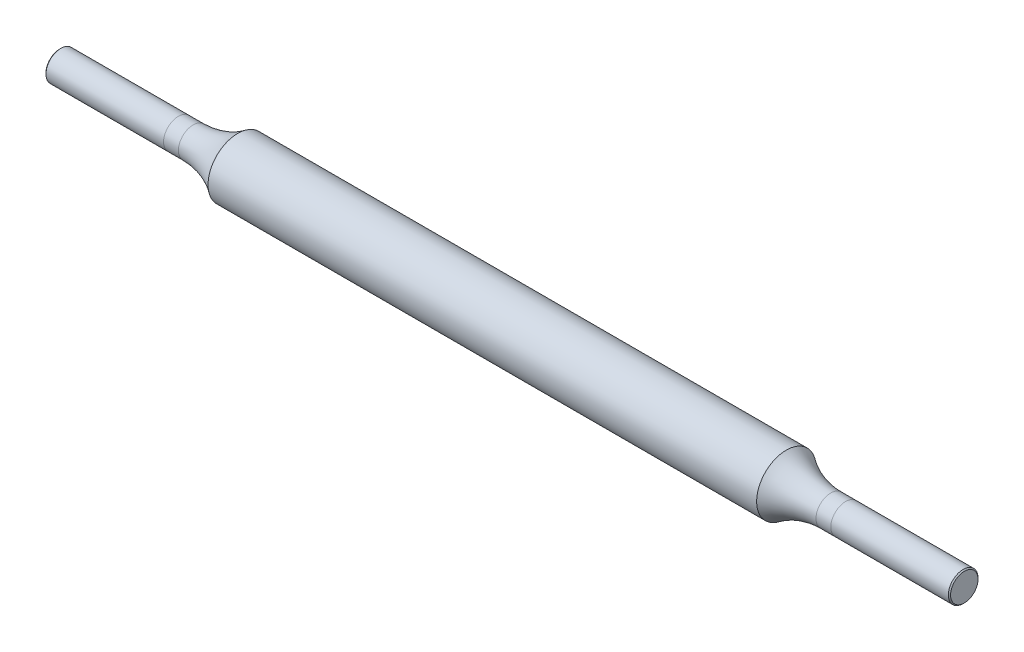
SolidWorks part; units mm, degrees
ref_plane "Front Plane" through (0, 0, 0) normal (0, 0, 1) x (1, 0, 0)
ref_plane "Top Plane" through (0, 0, 0) normal (0, 1, 0) x (1, 0, 0)
ref_plane "Right Plane" through (0, 0, 0) normal (1, 0, 0) x (0, 0, -1)
sketch "Sketch1" plane through (0, 0, 0) normal (0, 0, 1) x (1, 0, 0)
  line L0 (-30.49, 0) -> (30.49, 0)
  line L1 (30.49, 0) -> (30.49, 1)
  line L2 (-30.49, 0) -> (-30.49, 1)
  line L3 (-30.49, 1) -> (-21.49, 1)
  line L4 (-18.49, 2) -> (18.49, 2)
  line L5 (30.49, 1) -> (21.49, 1)
  arc A0 (-21.49, 1) -> (-18.49, 2) centre (-21.49, 6) ccw
  arc A1 (18.49, 2) -> (21.49, 1) centre (21.49, 6) ccw
  point P2 (0, 0)
  point P9 (0, 2)
  dimension "D6" = 3
  dimension "D1" = 60.98
  dimension "D2" = 1
  dimension "D3" = 9
  dimension "D4" = 9
  dimension "D5" = 2
revolve "Revolve1" add sketch "Sketch1" angle 360 about L0
sketch "Sketch2" plane through (0, 0, 0) normal (0, 0, 1) x (1, 0, 0)
  line L0 (-22.49, 6.0689) -> (-22.49, -8.5316)
  line L1 (22.49, 6.0689) -> (22.49, -7.3752)
  line L2 (-30.49, 1) -> (-30.49, -1) construction
  line L3 (30.49, -1) -> (30.49, 1) construction
  dimension "D1" = 8
  dimension "D2" = 8
split line "Split Line1"
chamfer "Chamfer1" distance 0.075 angle 45 2 edges at (-30.49, 0, 1) (30.49, 0, 1)
